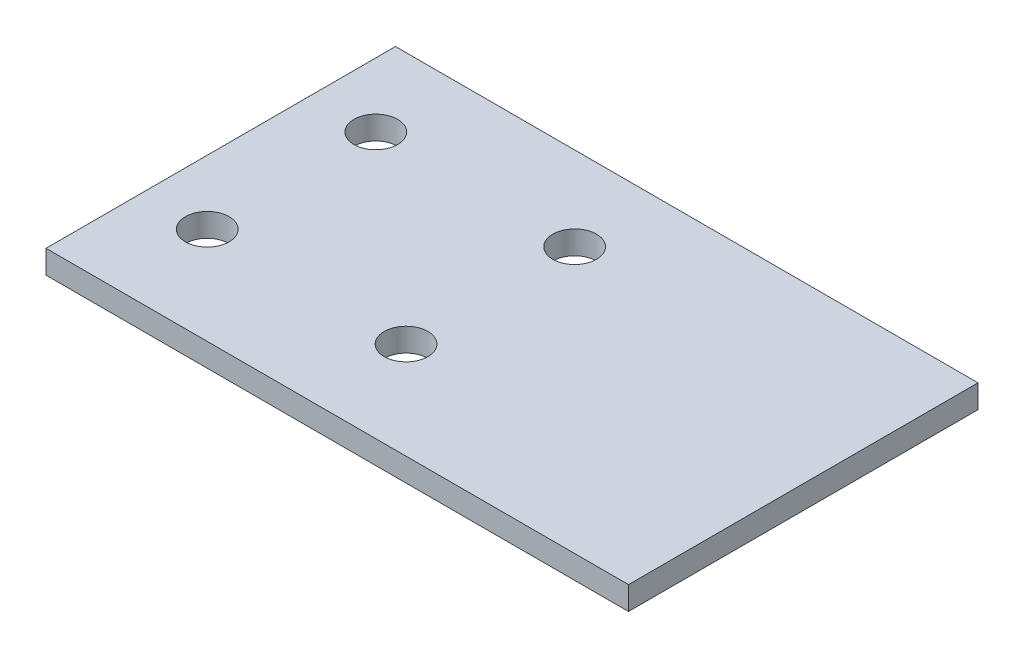
SolidWorks part; units mm, degrees
ref_plane "Front Plane" through (0, 0, 0) normal (0, 0, 1) x (1, 0, 0)
ref_plane "Top Plane" through (0, 0, 0) normal (0, 1, 0) x (1, 0, 0)
ref_plane "Right Plane" through (0, 0, 0) normal (1, 0, 0) x (0, 0, -1)
sketch "Sketch1" plane through (0, 0, 0) normal (0, 1, 0) x (1, 0, 0)
  line L0 (-63.5, 38.1) -> (63.5, -38.1) construction
  line L1 (-63.5, 38.1) -> (63.5, 38.1)
  line L2 (-63.5, 38.1) -> (-63.5, -38.1)
  line L3 (-63.5, -38.1) -> (63.5, -38.1)
  line L4 (63.5, 38.1) -> (63.5, -38.1)
  point P4 (0, 0)
  dimension "D1" = 76.2
  dimension "D2" = 127
extrude "Boss-Extrude1" add sketch "Sketch1" along normal blind 5.08
hole_wizard "3/8 (0.375) Diameter Hole1" positions "Sketch6" profile "Sketch7" hole size "3/8" standard "ANSI Inch" end condition through all
sketch "Sketch6" plane through (0, 5.08, 0) normal (0, 1, 0) x (-1, 0, 0)
  point P0 (49.5183, -19.8217)
  point P2 (49.5183, 16.9294)
  point P4 (6.1675, 16.9294)
  point P6 (6.1675, -19.8217)
sketch "Sketch7" plane through (-49.5183, 5.08, -19.8217) normal (1, 0, 0) x (0, 0, 1)
  line L0 (0, 0) -> (0, 5.08)
  line L1 (0, 5.08) -> (4.7625, 5.08)
  line L2 (4.7625, 5.08) -> (4.7625, 0)
  line L5 (4.7625, 0) -> (0, 0)
  line L11 (0, -6.35) -> (0, 107.95) construction
  dimension "Thru Hole Dia." = 9.525
  dimension "Thru Hole Depth" = 5.08
